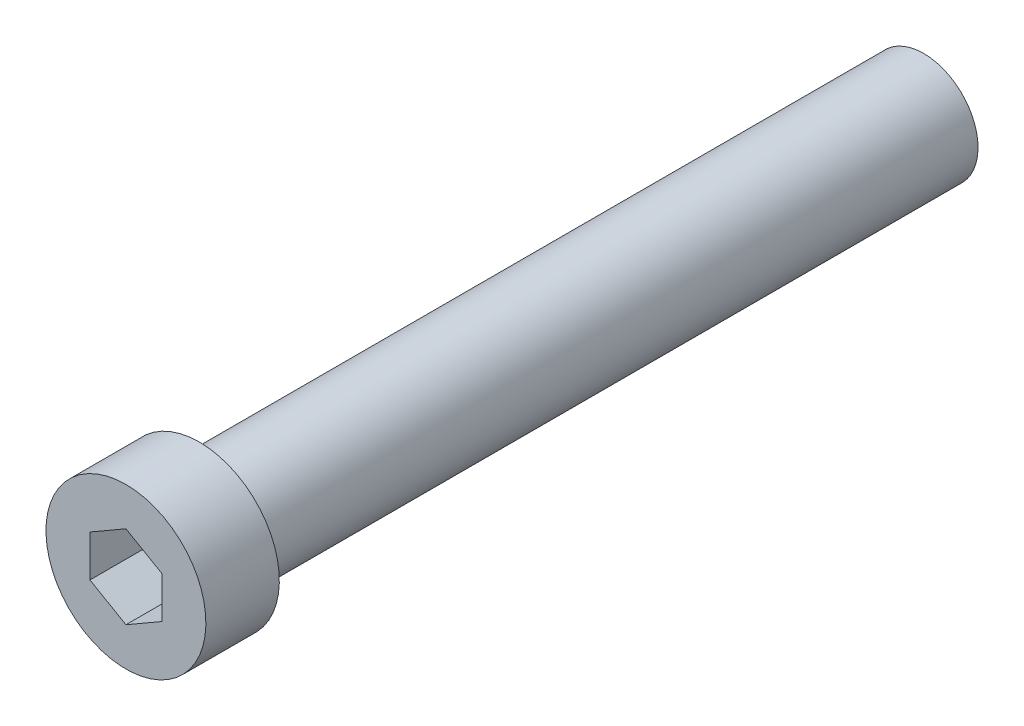
SolidWorks part; units mm, degrees
ref_plane "前视基准面" through (0, 0, 0) normal (0, 0, 1) x (1, 0, 0)
ref_plane "上视基准面" through (0, 0, 0) normal (0, 1, 0) x (1, 0, 0)
ref_plane "右视基准面" through (0, 0, 0) normal (1, 0, 0) x (0, 0, -1)
ref_plane "基准面1" through (0, 0, 0) normal (0, -1, 0) x (1, 0, 0)
sketch "草图1" plane through (0, 0, 0) normal (0, -1, 0) x (1, 0, 0)
  line L0 (2.208, 2.028) -> (0, 2.028)
  line L1 (0, 2.028) -> (0, 0)
  line L2 (0, 0) -> (2.208, 0)
  line L3 (2.208, 0) -> (2.208, 2.028)
  line L4 (0, 2.028) -> (0, 0) construction
revolve "旋转1" add sketch "草图1" angle 360 about L4
sketch "草图2" plane through (0, 0, 0) normal (0, 0, -1) x (-1, 0, 0)
  circle A0 centre (0, 0) radius 1.5
extrude "凸台-拉伸1" add sketch "草图2" along normal blind 20
sketch "草图3" plane through (0, 0, 2.028) normal (0, 0, 1) x (1, 0, 0)
  line L0 (0.9936, -0.5737) -> (0.9936, 0.5737)
  line L1 (0.9936, 0.5737) -> (0, 1.1473)
  line L2 (0, 1.1473) -> (-0.9936, 0.5737)
  line L3 (-0.9936, 0.5737) -> (-0.9936, -0.5737)
  line L4 (-0.9936, -0.5737) -> (0, -1.1473)
  line L5 (0, -1.1473) -> (0.9936, -0.5737)
extrude "切除-拉伸1" cut sketch "草图3" against normal blind 1.872
